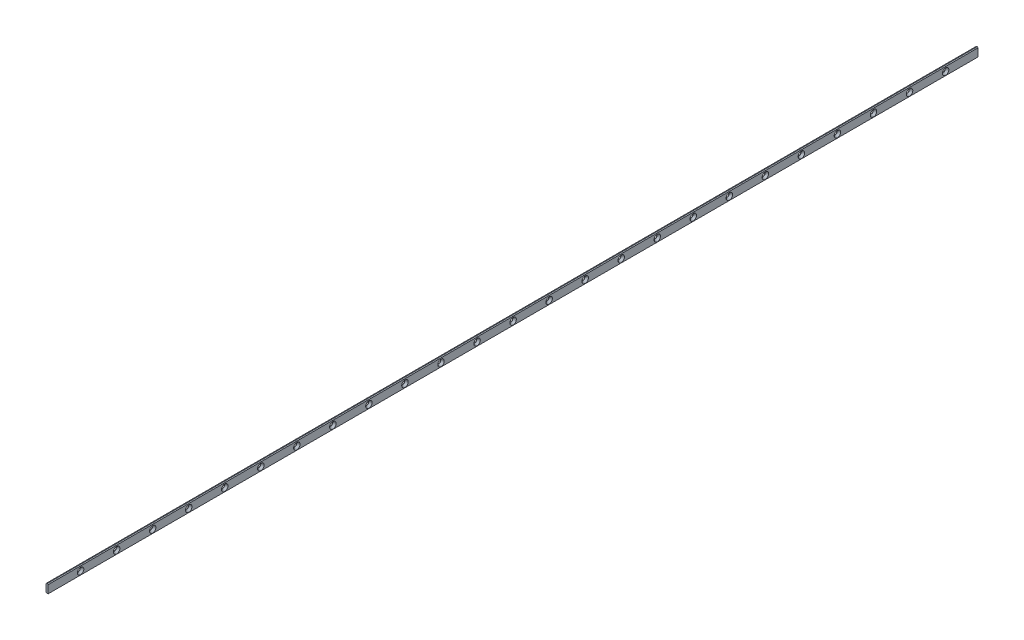
SolidWorks part; units mm, degrees
material "Plain Carbon Steel"
ref_plane "Front Plane" through (0, 0, 0) normal (0, 0, 1) x (1, 0, 0)
ref_plane "Top Plane" through (0, 0, 0) normal (0, 1, 0) x (1, 0, 0)
ref_plane "Right Plane" through (0, 0, 0) normal (1, 0, 0) x (0, 0, -1)
sketch "Sketch1" plane through (0, 0, 0) normal (0, 0, 1) x (1, 0, 0)
  line L1 (-1.5, -6) -> (1.5, -6)
  line L2 (-1.5, -6) -> (-1.5, 6)
  line L3 (-1.5, 6) -> (1.5, 6)
  line L4 (1.5, -6) -> (1.5, 6)
  line L5 (-1.5, -6) -> (1.5, 6) construction
  line L6 (-1.5, 6) -> (1.5, -6) construction
  point P0 (0, 0)
  dimension "D1" = 12
  dimension "D2" = 3
extrude "Boss-Extrude1" add sketch "Sketch1" along normal mid plane 1290
sketch "Sketch2" plane through (1.5, 0, 0) normal (1, 0, 0) x (0, 0, -1)
  line L0 (-645, -1) -> (645, -1) construction
  line L3 (-645, -6) -> (-645, 6) construction
  line L4 (645, -6) -> (645, 6) construction
  line L5 (-645, -6) -> (645, -6) construction
  circle A0 centre (0, -1) radius 2
  dimension "D2" = 4
  dimension "D1" = 5
extrude "Cut-Extrude1" cut sketch "Sketch2" against normal blind 10
chamfer "Chamfer1" distance 2.5 angle 45 1 edges at (1.5, -1, -2)
chamfer "Chamfer2" distance 1 angle 45 2 edges at (-1.5, 6, 0) (1.5, 6, 0)
pattern_linear "LPattern1" count 13 spacing 50 along (0, 0, -1) count 13 spacing 50 along (0, 0, 1) of "Cut-Extrude1", "Chamfer1"
